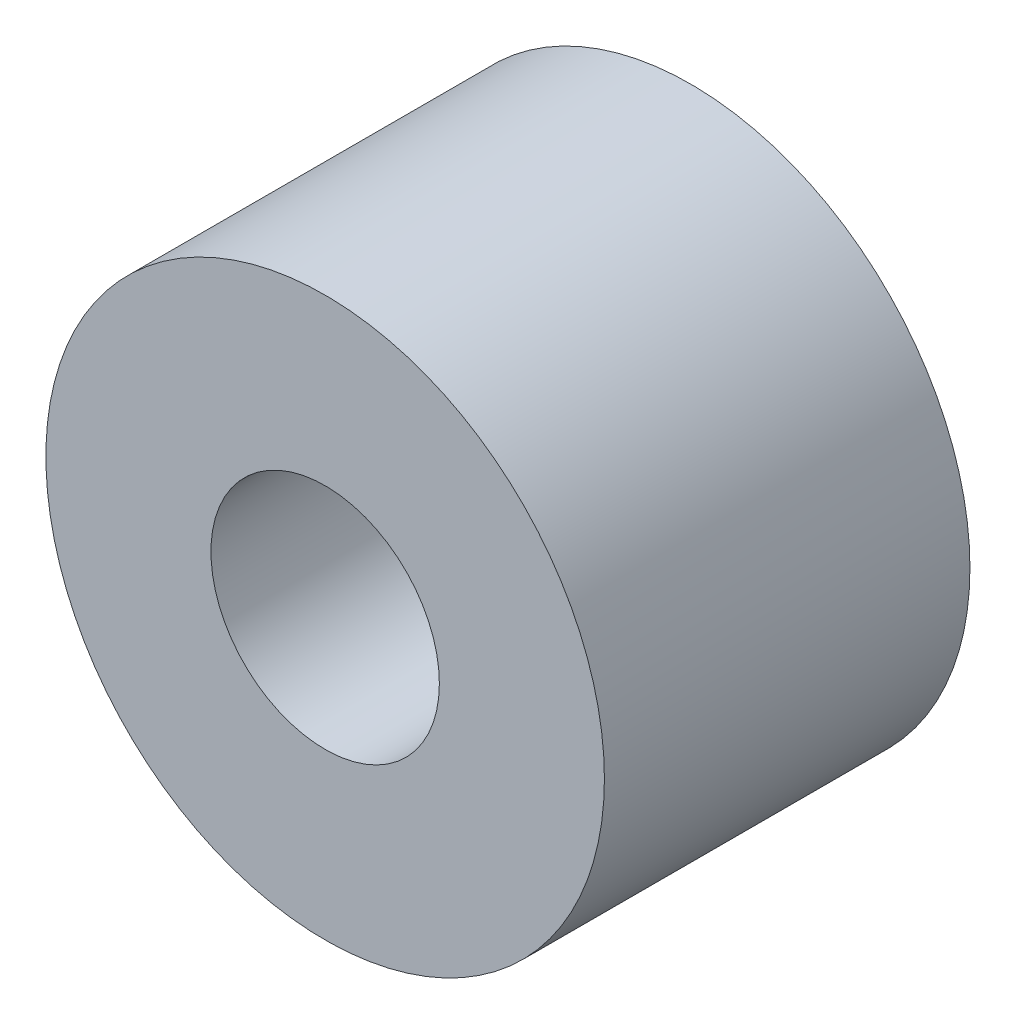
SolidWorks part; units mm, degrees
ref_plane "Front Plane" through (0, 0, 0) normal (0, 0, 1) x (1, 0, 0)
ref_plane "Top Plane" through (0, 0, 0) normal (0, 1, 0) x (1, 0, 0)
ref_plane "Right Plane" through (0, 0, 0) normal (1, 0, 0) x (0, 0, -1)
ref_plane "Plane1" through (0, 0, 334) normal (0, 0, 1) x (1, 0, 0)
sketch "Sketch1" plane through (0, 0, 334) normal (0, 0, 1) x (1, 0, 0)
  circle A0 centre (300, 300) radius 6.1122
  circle A1 centre (300, 300) radius 2.5
extrude "Boss-Extrude1" add sketch "Sketch1" along normal blind 8
